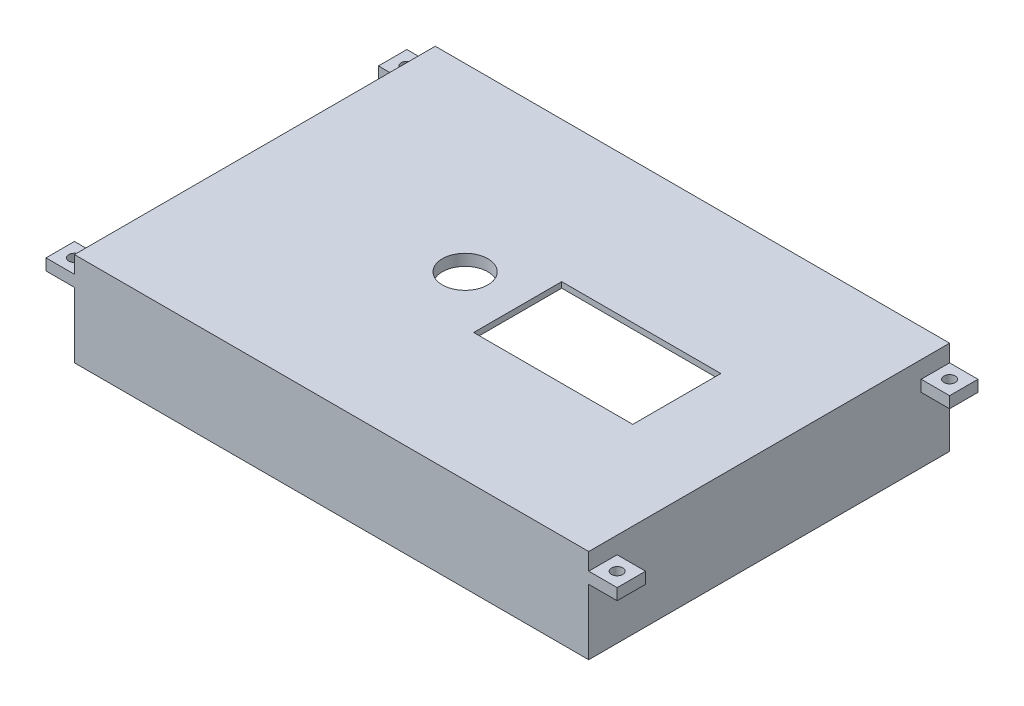
SolidWorks part; units mm, degrees
ref_plane "Front Plane" through (0, 0, 0) normal (0, 0, 1) x (1, 0, 0)
ref_plane "Top Plane" through (0, 0, 0) normal (0, 1, 0) x (1, 0, 0)
ref_plane "Right Plane" through (0, 0, 0) normal (1, 0, 0) x (0, 0, -1)
sketch "Sketch1" plane through (0, 0, 0) normal (0, 1, 0) x (1, 0, 0)
  line L1 (-43.25, -29.75) -> (43.25, -29.75)
  line L2 (-43.25, -29.75) -> (-43.25, 29.75)
  line L3 (-43.25, 29.75) -> (43.25, 29.75)
  line L4 (43.25, -29.75) -> (43.25, 29.75)
  line L5 (-43.25, -29.75) -> (43.25, 29.75) construction
  line L6 (-43.25, 29.75) -> (43.25, -29.75) construction
  point P0 (0, 0)
  dimension "D1" = 86.5
  dimension "D2" = 59.5
extrude "Boss-Extrude3" add sketch "Sketch1" against normal blind 16.5
sketch "Sketch5" plane through (0, -16.5, 0) normal (0, -1, 0) x (1, 0, 0)
  line L1 (-41.5, -27.75) -> (41.5, -27.75)
  line L2 (-41.5, -27.75) -> (-41.5, 27.75)
  line L3 (-41.5, 27.75) -> (41.5, 27.75)
  line L4 (41.5, -27.75) -> (41.5, 27.75)
  line L5 (-41.5, -27.75) -> (41.5, 27.75) construction
  line L6 (-41.5, 27.75) -> (41.5, -27.75) construction
  point P0 (0, 0)
  dimension "D1" = 83
  dimension "D2" = 55.5
extrude "Cut-Extrude2" cut sketch "Sketch5" against normal blind 10
sketch "Sketch6" plane through (0, 0, 0) normal (0, 1, 0) x (1, 0, 0)
  line L0 (1.75, -8.5) -> (29.75, 7) construction
  line L1 (-41.25, 27.5) -> (41.25, 27.5) construction
  line L2 (-41.25, 27.5) -> (-41.25, -27.5) construction
  line L3 (-41.25, -27.5) -> (41.25, -27.5) construction
  line L4 (41.25, 27.5) -> (41.25, -27.5) construction
  line L5 (-14.25, 6) -> (-2.25, -6) construction
  line L7 (1.75, -8.5) -> (29.75, -8.5)
  line L8 (1.75, -8.5) -> (1.75, 7)
  line L9 (1.75, 7) -> (29.75, 7)
  line L10 (29.75, -8.5) -> (29.75, 7)
  line L11 (1.75, 7) -> (29.75, -8.5) construction
  line L12 (-2.25, -6) -> (-14.25, -6) construction
  line L13 (2.25, 6.5) -> (29.25, 6.5) construction
  line L14 (2.25, 6.5) -> (2.25, -8) construction
  line L15 (2.25, -8) -> (29.25, -8) construction
  line L16 (29.25, 6.5) -> (29.25, -8) construction
  line L17 (2.25, 6.5) -> (29.25, -8) construction
  line L18 (2.25, -8) -> (29.25, 6.5) construction
  line L19 (-2.25, -6) -> (-2.25, 6) construction
  line L20 (-2.25, 6) -> (-14.25, 6) construction
  line L21 (-14.25, -6) -> (-14.25, 6) construction
  line L22 (-14.25, -6) -> (-2.25, 6) construction
  circle A0 centre (-8.25, 0) radius 4
  point P0 (0, 0)
  point P10 (15.75, -0.75)
  dimension "D13" = 8
  dimension "D1" = 82.5
  dimension "D2" = 55
  dimension "D3" = 15.5
  dimension "D4" = 28
  dimension "D5" = 20.5
  dimension "D6" = 11.5
  dimension "D7" = 14.5
  dimension "D8" = 27
  dimension "D9" = 12
  dimension "D10" = 12
  dimension "D11" = 4.5
  dimension "D12" = 21.5
extrude "Cut-Extrude5" cut sketch "Sketch6" against normal blind 6.5
sketch "Sketch10" plane through (0, -6.5, 0) normal (0, -1, 0) x (1, 0, 0)
  line L0 (-41.5, 27.75) -> (-41.5, -27.75) construction
  line L1 (-39.5, -26.4252) -> (39.5, -26.4252)
  line L2 (-39.5, -26.4252) -> (-39.5, 25.75)
  line L3 (-39.5, 25.75) -> (39.5, 25.75)
  line L4 (39.5, -26.4252) -> (39.5, 25.75)
  line L5 (41.5, -27.75) -> (41.5, 27.75) construction
  line L6 (41.5, 27.75) -> (-41.5, 27.75) construction
  dimension "D1" = 2
  dimension "D2" = 2
  dimension "D3" = 2
extrude "Cut-Extrude7" cut sketch "Sketch10" against normal blind 4.5
sketch "Sketch12" plane through (0, -2, 0) normal (0, -1, 0) x (1, 0, 0)
  line L0 (29.75, 8.5) -> (1.75, 8.5) construction
  line L1 (0.75, -13) -> (30.75, -13)
  line L2 (0.75, -13) -> (0.75, 19.5)
  line L3 (0.75, 19.5) -> (30.75, 19.5)
  line L4 (30.75, -13) -> (30.75, 19.5)
  line L5 (1.75, -7) -> (29.75, -7) construction
  line L6 (29.75, -7) -> (29.75, 8.5) construction
  line L7 (1.75, 8.5) -> (1.75, -7) construction
  dimension "D1" = 11
  dimension "D2" = 6
  dimension "D3" = 1
  dimension "D4" = 1
extrude "Cut-Extrude9" cut sketch "Sketch12" against normal blind 1
sketch "Sketch13" plane through (0, -2, 0) normal (0, -1, 0) x (1, 0, 0)
  line L1 (-2.25, -6) -> (-14.25, -6) construction
  line L2 (-2.25, -6) -> (-2.25, 6) construction
  line L3 (-2.25, 6) -> (-14.25, 6) construction
  line L4 (-14.25, -6) -> (-14.25, 6) construction
sketch "Sketch15" plane through (0, -16.5, 0) normal (0, -1, 0) x (1, 0, 0)
  line L0 (-41.5, -27.75) -> (41.5, -27.75) construction
  line L1 (-29.3783, -27.75) -> (-27.9168, -27.75)
  line L2 (-29.3783, -27.75) -> (-29.3783, -29.75)
  line L3 (-29.3783, -29.75) -> (-27.9168, -29.75)
  line L4 (-27.9168, -27.75) -> (-27.9168, -29.75)
  line L6 (43.25, -29.75) -> (45.25, -29.75)
  line L7 (43.25, -29.75) -> (43.25, 31.75)
  line L8 (43.25, 31.75) -> (45.25, 31.75)
  line L9 (45.25, -29.75) -> (45.25, 31.75)
  line L10 (43.25, 29.75) -> (-45.25, 29.75)
  line L11 (43.25, 29.75) -> (43.25, 31.75)
  line L12 (43.25, 31.75) -> (-45.25, 31.75)
  line L13 (-45.25, 29.75) -> (-45.25, 31.75)
  line L14 (-43.25, 29.75) -> (-45.25, 29.75)
  line L15 (-43.25, 29.75) -> (-43.25, -31.75)
  line L16 (-43.25, -31.75) -> (-45.25, -31.75)
  line L17 (-45.25, 29.75) -> (-45.25, -31.75)
  line L18 (-43.25, -29.75) -> (45.25, -29.75)
  line L19 (-43.25, -29.75) -> (-43.25, -31.75)
  line L20 (-43.25, -31.75) -> (45.25, -31.75)
  line L21 (45.25, -29.75) -> (45.25, -31.75)
  dimension "D1" = 2
  dimension "D2" = 2
  dimension "D3" = 2
  dimension "D4" = 2
  dimension "D5" = 2
extrude "Boss-Extrude4" add sketch "Sketch15" against normal blind 16.5 contours L13 L10 L8 L7 L12 | L10 L17 L16 L15 L11 | L21 L6 L13 L15 L20 | L6 L9 L8 L7
sketch "Sketch16" plane through (0, -16.5, 0) normal (0, -1, 0) x (1, 0, 0)
  line L0 (41.5, 27.75) -> (-41.5, 27.75) construction
  line L1 (-29, 27.75) -> (-26, 27.75)
  line L2 (-29, 27.75) -> (-29, 30.75)
  line L3 (-29, 30.75) -> (-26, 30.75)
  line L4 (-26, 27.75) -> (-26, 30.75)
  line L5 (-41.5, 27.75) -> (-41.5, -27.75) construction
  line L6 (26, 27.75) -> (29, 27.75)
  line L7 (26, 27.75) -> (26, 30.75)
  line L8 (26, 30.75) -> (29, 30.75)
  line L9 (29, 27.75) -> (29, 30.75)
  line L10 (41.5, -27.75) -> (41.5, 27.75) construction
  line L11 (41.5, -27.75) -> (41.5, 27.75) construction
  line L12 (41.5, 24.25) -> (44.5, 24.25)
  line L13 (41.5, 24.25) -> (41.5, 21.25)
  line L14 (41.5, 21.25) -> (44.5, 21.25)
  line L15 (44.5, 24.25) -> (44.5, 21.25)
  line L16 (41.5, 0) -> (45.25, 0) construction
  line L17 (45.25, -31.75) -> (45.25, 31.75) construction
  line L18 (41.5, -21.25) -> (44.5, -21.25)
  line L19 (44.5, -24.25) -> (44.5, -21.25)
  line L20 (41.5, -24.25) -> (44.5, -24.25)
  line L21 (41.5, -24.25) -> (41.5, -21.25)
  line L22 (41.5, 0) -> (41.5, -22.75) construction
  line L23 (41.5, -11.375) -> (45.25, -11.375) construction
  line L24 (41.5, 1.5) -> (41.5, -1.5)
  line L25 (41.5, 1.5) -> (44.5, 1.5)
  line L26 (44.5, 1.5) -> (44.5, -1.5)
  line L27 (41.5, -1.5) -> (44.5, -1.5)
  line L28 (41.5, 27.75) -> (-41.5, 27.75) construction
  dimension "D1" = 12.5
  dimension "D2" = 3
  dimension "D3" = 3
  dimension "D4" = 12.5
  dimension "D5" = 3.5
  dimension "D6" = 3
  dimension "D7" = 3
  dimension "D8" = 0
extrude "Cut-Extrude11" cut sketch "Sketch16" against normal blind 8
sketch "Sketch17" plane through (0, -2, 0) normal (0, -1, 0) x (1, 0, 0)
  line L0 (-6.1394, -3.3978) -> (-7.6086, -1.0325)
  circle A0 centre (-8.25, 0) radius 4 construction
sketch "Sketch19" plane through (0, -1, 0) normal (0, -1, 0) x (1, 0, 0)
  line L0 (1.75, -7) -> (0.75, -7) construction
  line L1 (0.75, 19.5) -> (0.75, -13) construction
sketch "Sketch20" plane through (0.75, 0, 0) normal (1, 0, 0) x (0, 0, -1)
  line L0 (7, -1) -> (7, -2) construction
  line L1 (-19.5, -2) -> (13, -2) construction
sketch "Sketch21" plane through (0, -16.5, 0) normal (0, -1, 0) x (1, 0, 0)
  line L0 (-50.25, 31.75) -> (-45.25, 26.75) construction
  line L1 (-45.25, 31.75) -> (-50.25, 31.75)
  line L2 (-45.25, 31.75) -> (-45.25, 26.75)
  line L3 (-45.25, 26.75) -> (-50.25, 26.75)
  line L4 (-50.25, 31.75) -> (-50.25, 26.75)
  line L5 (-50.25, 26.75) -> (-45.25, 31.75) construction
  line L6 (0, 31.75) -> (0, 27.75) construction
  line L7 (45.25, 31.75) -> (-45.25, 31.75) construction
  line L8 (26, 27.75) -> (-26, 27.75) construction
  line L9 (45.25, 26.75) -> (50.25, 26.75)
  line L10 (50.25, 31.75) -> (50.25, 26.75)
  line L11 (45.25, 31.75) -> (50.25, 31.75)
  line L12 (45.25, 31.75) -> (45.25, 26.75)
  line L13 (-45.25, 0) -> (-41.5, 0) construction
  line L14 (-45.25, -31.75) -> (-45.25, 31.75) construction
  line L15 (-41.5, 27.75) -> (-41.5, -27.75) construction
  line L16 (45.25, -31.75) -> (45.25, -26.75)
  line L17 (45.25, -31.75) -> (50.25, -31.75)
  line L18 (50.25, -31.75) -> (50.25, -26.75)
  line L19 (45.25, -26.75) -> (50.25, -26.75)
  line L20 (-45.25, -26.75) -> (-50.25, -26.75)
  line L21 (-50.25, -31.75) -> (-50.25, -26.75)
  line L22 (-45.25, -31.75) -> (-50.25, -31.75)
  line L23 (-45.25, -31.75) -> (-45.25, -26.75)
  circle A0 centre (-47.75, 29.25) radius 1
  circle A1 centre (47.75, 29.25) radius 1
  circle A2 centre (47.75, -29.25) radius 1
  circle A3 centre (-47.75, -29.25) radius 1
  dimension "D3" = 2
  dimension "D1" = 5
  dimension "D2" = 5
extrude "Boss-Extrude6" add sketch "Sketch21" against normal blind 13.5
sketch "Sketch23" plane through (0, -16.5, 0) normal (0, -1, 0) x (-1, 0, 0)
  line L0 (-50.25, 26.75) -> (-45.25, 26.75) construction
  line L1 (-50.25, 31.75) -> (-45.25, 31.75)
  line L2 (-50.25, 31.75) -> (-50.25, 26.75)
  line L3 (-50.25, 26.75) -> (-45.25, 26.75)
  line L4 (-45.25, 31.75) -> (-45.25, 26.75)
extrude "Cut-Extrude12" cut sketch "Sketch23" against normal blind 11.5
sketch "Sketch24" plane through (0, -16.5, 0) normal (0, -1, 0) x (1, 0, 0)
  line L1 (45.25, 26.75) -> (50.25, 26.75)
  line L2 (45.25, 26.75) -> (45.25, 31.75)
  line L3 (45.25, 31.75) -> (50.25, 31.75)
  line L4 (50.25, 26.75) -> (50.25, 31.75)
extrude "Cut-Extrude13" cut sketch "Sketch24" against normal blind 11.5
sketch "Sketch25" plane through (0, -16.5, 0) normal (0, -1, 0) x (1, 0, 0)
  line L1 (-45.25, 26.75) -> (-50.25, 26.75)
  line L2 (-45.25, 26.75) -> (-45.25, 31.75)
  line L3 (-45.25, 31.75) -> (-50.25, 31.75)
  line L4 (-50.25, 26.75) -> (-50.25, 31.75)
extrude "Cut-Extrude14" cut sketch "Sketch25" against normal blind 11.5
sketch "Sketch26" plane through (0, -16.5, 0) normal (0, -1, 0) x (-1, 0, 0)
  line L1 (45.25, 26.75) -> (50.25, 26.75)
  line L2 (45.25, 26.75) -> (45.25, 31.75)
  line L3 (45.25, 31.75) -> (50.25, 31.75)
  line L4 (50.25, 26.75) -> (50.25, 31.75)
extrude "Cut-Extrude15" cut sketch "Sketch26" against normal blind 11.5
